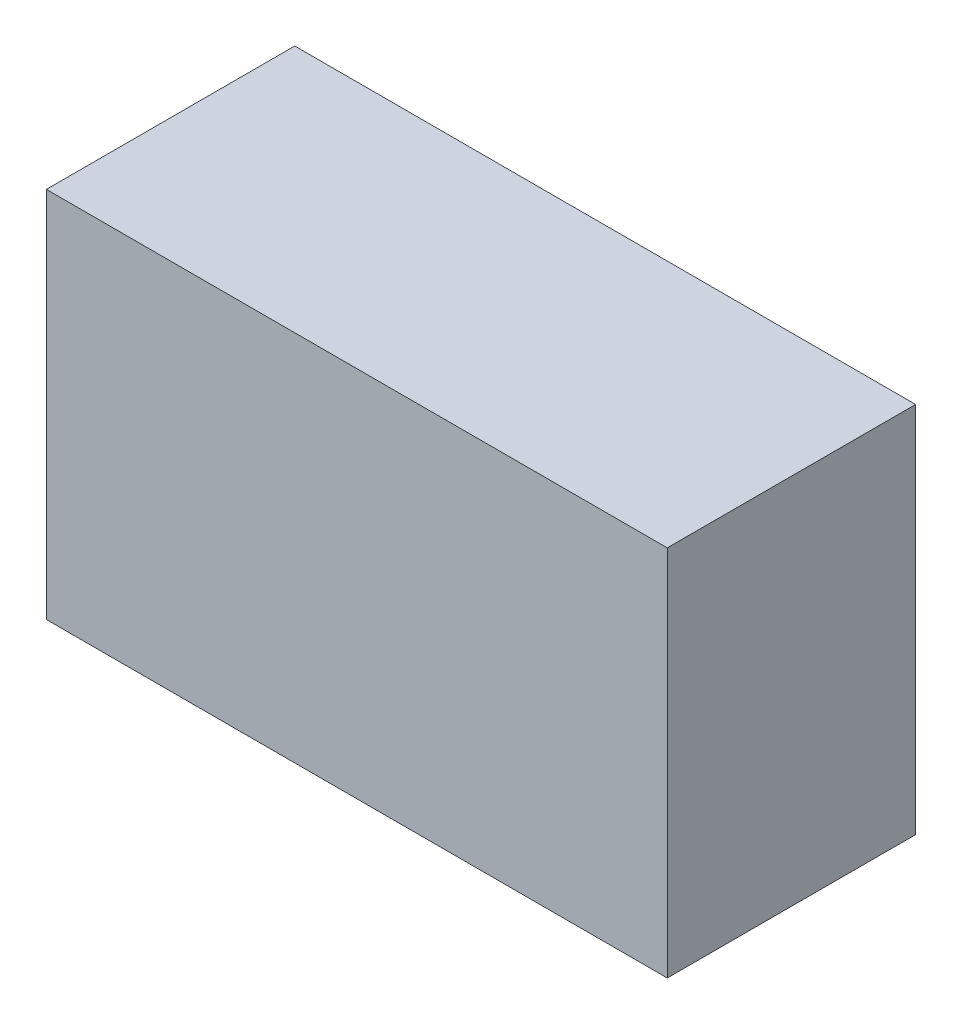
SolidWorks part; units mm, degrees
ref_plane "Front Plane" through (0, 0, 0) normal (0, 0, 1) x (1, 0, 0)
ref_plane "Top Plane" through (0, 0, 0) normal (0, 1, 0) x (1, 0, 0)
ref_plane "Right Plane" through (0, 0, 0) normal (1, 0, 0) x (0, 0, -1)
other "Configuration Table"
sketch "草图1" plane through (0, 0, 0) normal (0, 0, 1) x (1, 0, 0)
  line L1 (-25, -15) -> (25, -15)
  line L2 (-25, -15) -> (-25, 15)
  line L3 (-25, 15) -> (25, 15)
  line L4 (25, -15) -> (25, 15)
extrude "凸台-拉伸1" add sketch "草图1" along normal blind 20
